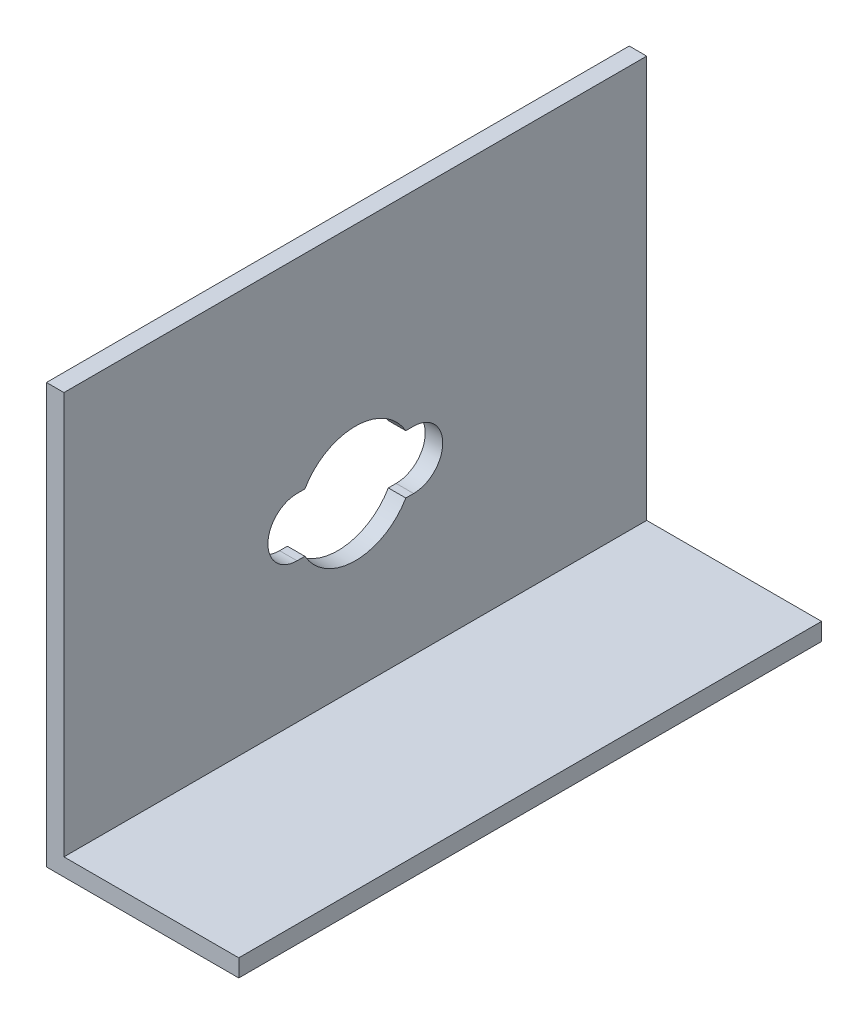
SolidWorks part; units mm, degrees
ref_plane "Front Plane" through (0, 0, 0) normal (0, 0, 1) x (1, 0, 0)
ref_plane "Top Plane" through (0, 0, 0) normal (0, 1, 0) x (1, 0, 0)
ref_plane "Right Plane" through (0, 0, 0) normal (1, 0, 0) x (0, 0, -1)
sketch "Sketch1" plane through (0, 0, 0) normal (0, 0, 1) x (1, 0, 0)
  line L0 (0, 72) -> (3, 72)
  line L1 (3, 3) -> (3, 72)
  line L2 (0, 72) -> (0, 0)
  line L3 (0, 0) -> (33, 0)
  line L4 (33, 0) -> (33, 3)
  line L5 (33, 3) -> (3, 3)
  point P6 (0, 0)
  point P8 (0, 0)
  point P9 (0, 0)
  dimension "D1" = 30
  dimension "D2" = 3
  dimension "D3" = 3
  dimension "D4" = 72
extrude "Boss-Extrude1" add sketch "Sketch1" along normal blind 100
sketch "Sketch2" plane through (0, 0, 0) normal (-1, 0, 0) x (0, 0, 1)
  line L0 (58.6603, 37) -> (60, 37)
  line L1 (40, 32) -> (60, 32) construction
  line L2 (40, 37) -> (41.3397, 37)
  line L3 (40, 27) -> (41.3397, 27)
  line L4 (58.6603, 27) -> (60, 27)
  line L5 (100, 0) -> (0, 0) construction
  line L7 (0, 72) -> (0, 0) construction
  arc A0 (40, 37) -> (40, 27) centre (40, 32) ccw
  arc A1 (60, 27) -> (60, 37) centre (60, 32) ccw
  arc A2 (58.6603, 37) -> (41.3397, 37) centre (50, 32) ccw
  arc A3 (41.3397, 27) -> (58.6603, 27) centre (50, 32) ccw
  point P2 (50, 32)
  point P17 (100, 47.5307)
  dimension "D1" = 5
  dimension "D3" = 20
  dimension "D6" = 5
  dimension "D2" = 20
  dimension "D4" = 5
  dimension "D5" = 5
  dimension "D7" = 10
  dimension "D8" = 10
  dimension "D9" = 1.3397
  dimension "D10" = 1.3397
  dimension "D11" = 32
  dimension "D12" = 50
extrude "Cut-Extrude1" cut sketch "Sketch2" against normal blind 100
